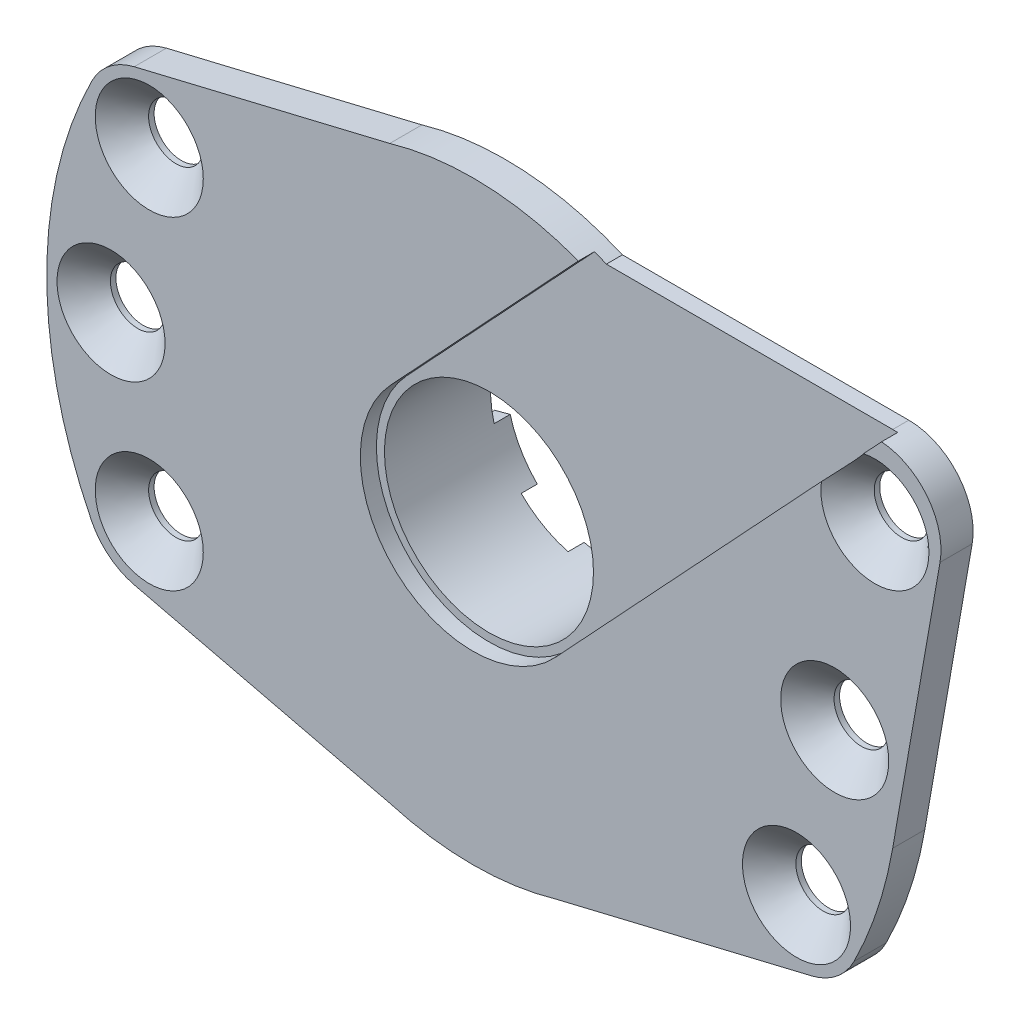
SolidWorks part; units mm, degrees
ref_plane "Спереди" through (0, 0, 0) normal (0, 0, 1) x (1, 0, 0)
ref_plane "Сверху" through (0, 0, 0) normal (0, 1, 0) x (1, 0, 0)
ref_plane "Справа" through (0, 0, 0) normal (1, 0, 0) x (0, 0, -1)
sketch "Эскиз1" plane through (0, 0, 0) normal (0, 0, 1) x (1, 0, 0)
  line L0 (-9.3783, -4.6892) -> (44711.9812, 22355.9906) construction
  line L1 (0, 0.385) -> (0, 50000.385) construction
  line L2 (-11.9154, 0) -> (49988.0846, 0) construction
  line L3 (0, 0) -> (-44721.3595, 22360.6798) construction
  line L4 (-5.1682, 17.7645) -> (-21.0579, 13.9519)
  line L5 (-5.1682, -17.7645) -> (-21.0579, -13.9519)
  line L6 (5.1682, -17.7645) -> (21.0579, -13.9519)
  line L7 (29.0494, 12.3123) -> (26.1054, -4.5561)
  line L8 (25.109, 17) -> (7.3, 17)
  arc A0 (-23.7023, 11.8512) -> (-23.7023, -11.8512) centre (0, 0) ccw
  arc A1 (-23.7023, 11.8512) -> (-21.0579, 13.9519) centre (-20.1246, 10.0623) cw
  arc A2 (7.3, 17) -> (-5.1682, 17.7645) centre (0, 0) ccw
  circle A3 centre (0, 0) radius 22.5 construction
  arc A4 (-23.7023, -11.8512) -> (-21.0579, -13.9519) centre (-20.1246, -10.0623) ccw
  arc A5 (23.7023, -11.8512) -> (21.0579, -13.9519) centre (20.1246, -10.0623) cw
  arc A6 (-5.1682, -17.7645) -> (5.1682, -17.7645) centre (0, 0) ccw
  arc A7 (26.1054, -4.5561) -> (23.7023, -11.8512) centre (0, 0) cw
  circle A9 centre (25, 12.5) radius 0.5
  circle A10 centre (22.5, 0) radius 0.5
  circle A11 centre (20.1246, -10.0623) radius 0.5
  circle A12 centre (-20.1246, -10.0623) radius 0.5
  circle A13 centre (-22.5, 0) radius 0.5
  circle A14 centre (-20.1246, 10.0623) radius 0.5
  circle A15 centre (0, 0) radius 6.5
  arc A16 (25.109, 17) -> (29.0494, 12.3123) centre (25.109, 13) cw
  dimension "D1" = 53
  dimension "D2" = 4
  dimension "D3" = 45
  dimension "D4" = 18.5011
  dimension "D6" = 17
  dimension "D10" = 1
  dimension "D11" = 1
  dimension "D12" = 1
  dimension "D13" = 1
  dimension "D14" = 13
  dimension "D15" = 4
  dimension "D7" = 53.13
  dimension "D8" = 25
  dimension "D9" = 12.5
  dimension "D16" = 99.9
  dimension "D5" = 49.942
extrude "Бобышка-Вытянуть2" add sketch "Эскиз1" along normal blind 2
hole_wizard "Зенковка для винта с потайной головкой и внутренним шестигранником M31" positions "Эскиз2" profile "Эскиз3" countersink size "M3" standard "ISO" end condition through all
sketch "Эскиз2" plane through (0, 0, 2) normal (0, 0, 1) x (1, 0, 0)
  point P0 (-20.1246, 10.0623)
  point P3 (-22.5, 0)
  point P6 (-20.1246, -10.0623)
  point P9 (20.1246, -10.0623)
  point P12 (22.5, 0)
  point P15 (25, 12.5)
sketch "Эскиз3" plane through (-20.1246, 10.0623, 2) normal (1, 0, 0) x (0, -1, 0)
  line L0 (0, 0) -> (0, 2)
  line L1 (0, 2) -> (1.7, 2)
  line L2 (1.7, 2) -> (1.7, 1.66)
  line L3 (1.7, 1.66) -> (3.36, 0)
  line L5 (3.36, 0) -> (0, 0)
  line L6 (-1.7, 1.66) -> (-3.36, 0) construction
  line L11 (0, -6.35) -> (0, 107.95) construction
  dimension "Диаметр сквозного отверстия" = 3.4
  dimension "Глубина сквозного отверстия" = 2
  dimension "Диаметр передней зенковки" = 6.72
  dimension "Угол передней зенковки" = 90
sketch "Эскиз4" plane through (0, 0, 0) normal (0, 0, -1) x (-1, 0, 0)
  circle A0 centre (0, 0) radius 8.5
  circle A1 centre (0, 0) radius 6.5
  dimension "D1" = 17
  dimension "D2" = 13
extrude "Бобышка-Вытянуть3" add sketch "Эскиз4" along normal blind 0.5
sketch "Эскиз5" plane through (0, 0, -0.5) normal (0, 0, -1) x (-1, 0, 0)
  circle A0 centre (0, 0) radius 6.5
  circle A1 centre (0, 0) radius 7.5
  dimension "D1" = 13
  dimension "D2" = 15
extrude "Бобышка-Вытянуть4" add sketch "Эскиз5" along normal blind 5.1
sketch "Эскиз6" plane through (0, 0, 2) normal (0, 0, 1) x (1, 0, 0)
  line L0 (-5.1195, 4.774) -> (15.3405, 26.7146)
  line L1 (5.1195, -4.774) -> (25.5794, 17.1666)
  line L2 (15.3405, 26.7146) -> (25.5794, 17.1666)
  line L3 (0, 0) -> (50000, 0) construction
  arc A0 (-5.1195, 4.774) -> (5.1195, -4.774) centre (0, 0) ccw
  dimension "D1" = 14
  dimension "D2" = 30
  dimension "D3" = 30
  dimension "D4" = 47
extrude "Вырез-Вытянуть1" cut sketch "Эскиз6" against normal blind 1
sketch "Эскиз7" plane through (0, 0, -5.6) normal (0, 0, -1) x (-1, 0, 0)
  line L0 (0, 0) -> (0, 50000) construction
  line L1 (0, 0) -> (12940.9523, 48296.2913) construction
  line L2 (0, 0) -> (-12940.9523, 48296.2913) construction
  line L3 (-1.9411, 7.2444) -> (-1.6823, 6.2785)
  line L4 (1.9411, 7.2444) -> (1.6823, 6.2785)
  line L5 (5.3033, 5.3033) -> (4.5962, 4.5962)
  line L6 (7.2444, 1.9411) -> (6.2785, 1.6823)
  line L7 (7.2444, -1.9411) -> (6.2785, -1.6823)
  line L8 (5.3033, -5.3033) -> (4.5962, -4.5962)
  line L9 (1.9411, -7.2444) -> (1.6823, -6.2785)
  line L10 (-1.9411, -7.2444) -> (-1.6823, -6.2785)
  line L11 (-5.3033, -5.3033) -> (-4.5962, -4.5962)
  line L12 (-7.2444, -1.9411) -> (-6.2785, -1.6823)
  line L13 (-7.2444, 1.9411) -> (-6.2785, 1.6823)
  line L14 (-5.3033, 5.3033) -> (-4.5962, 4.5962)
  arc A0 (-1.9411, 7.2444) -> (1.9411, 7.2444) centre (0, 0) cw
  arc A2 (-1.6823, 6.2785) -> (1.6823, 6.2785) centre (0, 0) cw
  arc A4 (5.3033, 5.3033) -> (7.2444, 1.9411) centre (0, 0) cw
  arc A5 (4.5962, 4.5962) -> (6.2785, 1.6823) centre (0, 0) cw
  arc A6 (7.2444, -1.9411) -> (5.3033, -5.3033) centre (0, 0) cw
  arc A7 (6.2785, -1.6823) -> (4.5962, -4.5962) centre (0, 0) cw
  arc A8 (1.9411, -7.2444) -> (-1.9411, -7.2444) centre (0, 0) cw
  arc A9 (1.6823, -6.2785) -> (-1.6823, -6.2785) centre (0, 0) cw
  arc A10 (-5.3033, -5.3033) -> (-7.2444, -1.9411) centre (0, 0) cw
  arc A11 (-4.5962, -4.5962) -> (-6.2785, -1.6823) centre (0, 0) cw
  arc A12 (-7.2444, 1.9411) -> (-5.3033, 5.3033) centre (0, 0) cw
  arc A13 (-6.2785, 1.6823) -> (-4.5962, 4.5962) centre (0, 0) cw
  point P35 (0, 0)
  dimension "D3" = 6.5
  dimension "D4" = 7.5
  dimension "D1" = 30
  dimension "D2" = 15
  dimension "D5" = 6
extrude "Бобышка-Вытянуть5" add sketch "Эскиз7" along normal blind 1
